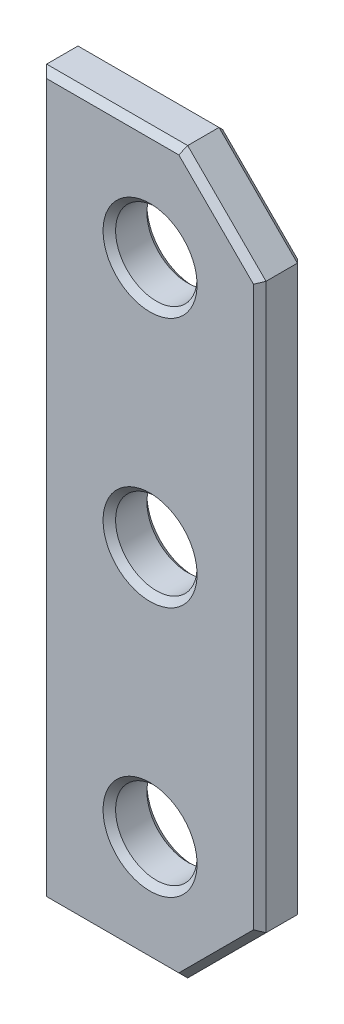
SolidWorks part; units mm, degrees
ref_plane "前视" through (0, 0, 0) normal (0, 0, 1) x (1, 0, 0)
ref_plane "上视" through (0, 0, 0) normal (0, 1, 0) x (1, 0, 0)
ref_plane "右视" through (0, 0, 0) normal (1, 0, 0) x (0, 0, -1)
sketch "草图1" plane through (0, 0, 0) normal (0, 0, 1) x (1, 0, 0)
  line L0 (35, 276.754) -> (35, -116.5623) construction
  line L1 (0, 0) -> (45, 0)
  line L2 (0, 0) -> (0, 230)
  line L3 (0, 230) -> (45, 230)
  line L4 (70, 25) -> (70, 205)
  line L5 (45, 230) -> (70, 205)
  line L6 (35, 115) -> (151.4714, 115) construction
  line L7 (45, 0) -> (70, 25)
  circle A0 centre (35, 35) radius 13
  circle A1 centre (35, 115) radius 13
  circle A2 centre (35, 195) radius 13
  dimension "D7" = 26
  dimension "D1" = 70
  dimension "D2" = 230
  dimension "D3" = 35
  dimension "D5" = 80
  dimension "D6" = 80
  dimension "D8" = 135
  dimension "D9" = 25
extrude "基体-拉伸" add sketch "草图1" along normal blind 14
chamfer "倒角1" distance 2 angle 45 18 edges at (48, 195, 0) (48, 35, 0) (22.5, 0, 0) (57.5, 12.5, 0) (70, 115, 0) (57.5, 217.5, 0) (22.5, 230, 0) (0, 115, 0) (48, 115, 0) (48, 195, 14) (48, 35, 14) (22.5, 230, 14) (57.5, 217.5, 14) (70, 115, 14) (57.5, 12.5, 14) (22.5, 0, 14) (0, 115, 14) (48, 115, 14)
